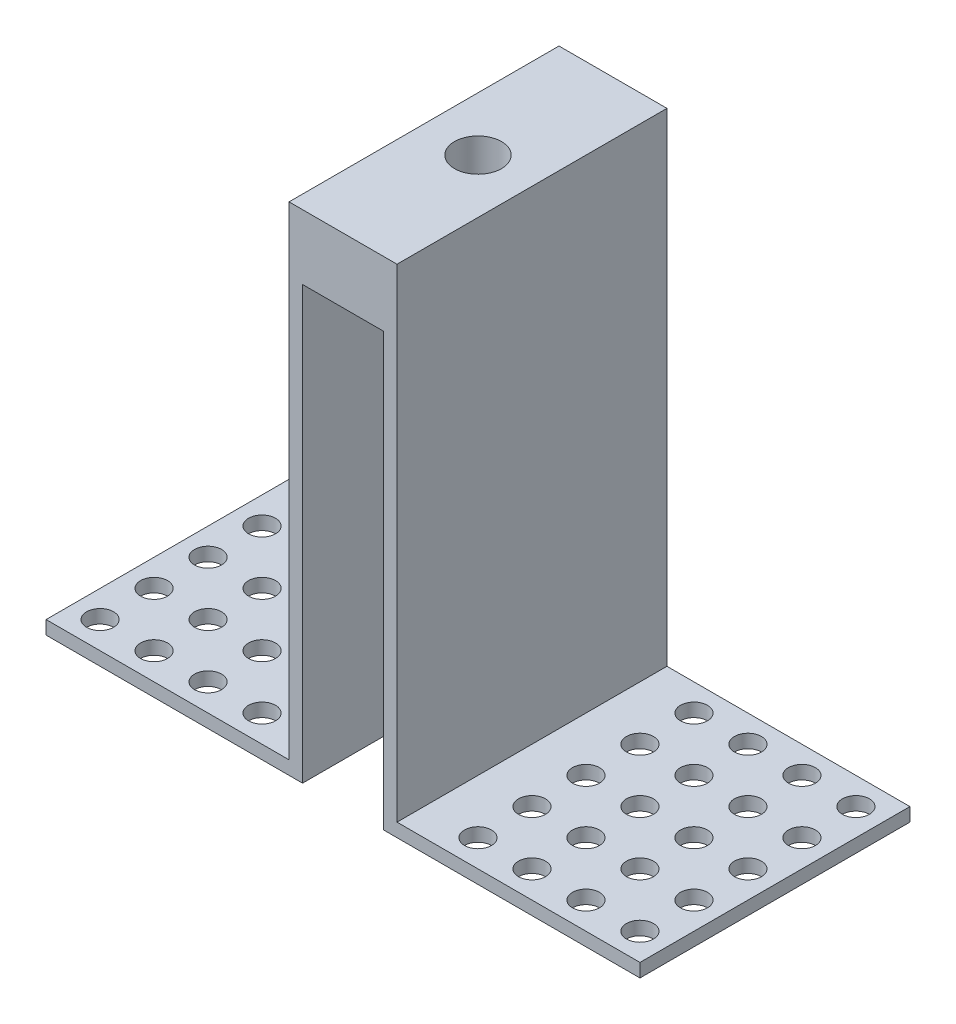
SolidWorks part; units mm, degrees
ref_plane "Front Plane" through (0, 0, 0) normal (0, 0, 1) x (1, 0, 0)
ref_plane "Top Plane" through (0, 0, 0) normal (0, 1, 0) x (1, 0, 0)
ref_plane "Right Plane" through (0, 0, 0) normal (1, 0, 0) x (0, 0, -1)
sketch "Sketch1" plane through (0, 0, 0) normal (0, 1, 0) x (1, 0, 0)
  line L1 (-12.7, -31.75) -> (12.7, -31.75)
  line L2 (-12.7, -31.75) -> (-12.7, 31.75)
  line L3 (-12.7, 31.75) -> (12.7, 31.75)
  line L4 (12.7, -31.75) -> (12.7, 31.75)
  line L5 (-12.7, -31.75) -> (12.7, 31.75) construction
  line L6 (-12.7, 31.75) -> (12.7, -31.75) construction
  circle A0 centre (0, 0) radius 5.5245
  dimension "D1" = 11.049
  dimension "D2" = 25.4
  dimension "D3" = 63.5
extrude "Boss-Extrude1" add sketch "Sketch1" along normal blind 15.24
sketch "Sketch2" plane through (0, 0, 31.75) normal (0, 0, 1) x (1, 0, 0)
  line L0 (-12.7, 0) -> (12.7, 0) construction
  line L1 (-9.525, 0) -> (-12.7, 0)
  line L2 (-9.525, 0) -> (-9.525, -101.6)
  line L3 (-9.525, -101.6) -> (-38.1, -101.6)
  line L4 (-12.7, 0) -> (-12.7, -98.425)
  line L6 (-12.7, -98.425) -> (-69.85, -98.425)
  line L7 (-12.7, 15.24) -> (-12.7, 0) construction
  line L8 (-38.1, -101.6) -> (-69.85, -101.6)
  line L9 (-69.85, -98.425) -> (-69.85, -101.6)
  line L10 (-38.1, -27.8623) -> (-38.1, -9.9747) construction
  point P9 (0, 0)
  point P11 (-32.2751, -101.6)
  point P12 (0, 0)
  point P13 (0, 0)
  point P16 (-41.9334, -47.625)
  dimension "D1" = 38.1
  dimension "D2" = 3.175
  dimension "D3" = 101.6
  dimension "D4" = 3.175
  dimension "D6" = 31.75
extrude "Boss-Extrude2" add sketch "Sketch2" against normal up to surface (63.5 mm away) up to face at (0, 7.62, -31.75)
mirror "Mirror1" about plane through (0, 0, 0) normal (1, 0, 0) of "Boss-Extrude2"
sketch "Sketch5" plane through (0, -98.425, 0) normal (0, 1, 0) x (1, 0, 0)
  line L0 (0, 0) -> (0, 70.0818) construction
  line L1 (0, 0) -> (-90.4616, 0) construction
  circle A0 centre (63.5, -25.4) radius 3.175
  circle A1 centre (50.8, -25.4) radius 3.175
  circle A2 centre (38.1, -25.4) radius 3.175
  circle A3 centre (25.4, -25.4) radius 3.175
  circle A4 centre (50.8, -12.7) radius 3.175
  circle A5 centre (38.1, -12.7) radius 3.175
  circle A6 centre (25.4, -12.7) radius 3.175
  circle A7 centre (50.8, 0) radius 3.175
  circle A8 centre (38.1, 0) radius 3.175
  circle A9 centre (25.4, 0) radius 3.175
  circle A10 centre (50.8, 12.7) radius 3.175
  circle A11 centre (38.1, 12.7) radius 3.175
  circle A12 centre (25.4, 12.7) radius 3.175
  circle A13 centre (50.8, 25.4) radius 3.175
  circle A14 centre (38.1, 25.4) radius 3.175
  circle A15 centre (25.4, 25.4) radius 3.175
  circle A16 centre (63.5, -12.7) radius 3.175
  circle A17 centre (63.5, 0) radius 3.175
  circle A18 centre (63.5, 12.7) radius 3.175
  circle A19 centre (63.5, 25.4) radius 3.175
  circle A20 centre (-63.5, 25.4) radius 3.175
  circle A21 centre (-63.5, 12.7) radius 3.175
  circle A22 centre (-63.5, 0) radius 3.175
  circle A23 centre (-63.5, -12.7) radius 3.175
  circle A24 centre (-25.4, 25.4) radius 3.175
  circle A25 centre (-38.1, 25.4) radius 3.175
  circle A26 centre (-50.8, 25.4) radius 3.175
  circle A27 centre (-25.4, 12.7) radius 3.175
  circle A28 centre (-38.1, 12.7) radius 3.175
  circle A29 centre (-50.8, 12.7) radius 3.175
  circle A30 centre (-25.4, 0) radius 3.175
  circle A31 centre (-38.1, 0) radius 3.175
  circle A32 centre (-50.8, 0) radius 3.175
  circle A33 centre (-25.4, -12.7) radius 3.175
  circle A34 centre (-38.1, -12.7) radius 3.175
  circle A35 centre (-50.8, -12.7) radius 3.175
  circle A36 centre (-25.4, -25.4) radius 3.175
  circle A37 centre (-38.1, -25.4) radius 3.175
  circle A38 centre (-50.8, -25.4) radius 3.175
  circle A39 centre (-63.5, -25.4) radius 3.175
  dimension "D1" = 6.35
  dimension "D2" = 63.5
  dimension "D3" = 25.4
extrude "Cut-Extrude3" cut sketch "Sketch5" against normal through all
